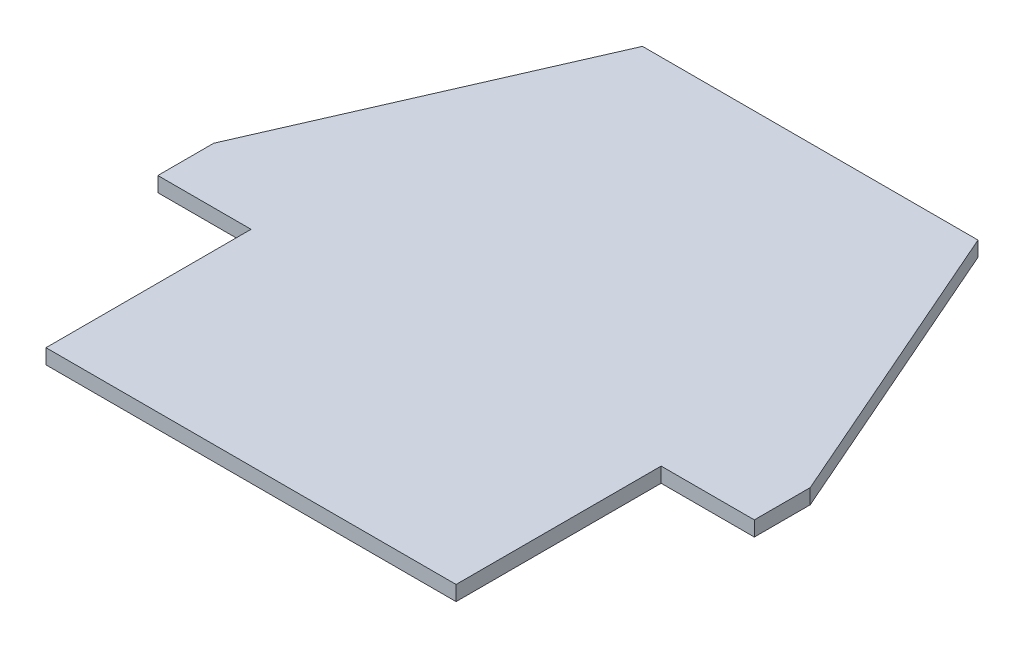
SolidWorks part; units mm, degrees
ref_plane "Alzado" through (0, 0, 0) normal (0, 0, 1) x (1, 0, 0)
ref_plane "Planta" through (0, 0, 0) normal (0, 1, 0) x (1, 0, 0)
ref_plane "Vista lateral" through (0, 0, 0) normal (1, 0, 0) x (0, 0, -1)
sketch "Croquis1" plane through (0, 0, 0) normal (0, 1, 0) x (1, 0, 0)
  line L0 (0, -196.1598) -> (0, 9611.8324) construction
  line L1 (80, 0) -> (-80, 0)
  line L2 (80, 0) -> (80, 70)
  line L3 (80, 70) -> (45, 150)
  line L4 (45, 150) -> (-45, 150)
  line L5 (-80, 0) -> (-80, 70)
  line L6 (-80, 70) -> (-45, 150)
  line L7 (80, 55) -> (55, 55)
  line L8 (55, 55) -> (55, 0)
  line L9 (-55, 55) -> (-55, 0)
  line L10 (-80, 55) -> (-55, 55)
  dimension "D1" = 160
  dimension "D2" = 90
  dimension "D3" = 150
  dimension "D4" = 80
  dimension "D5" = 55
  dimension "D6" = 25
extrude "Saliente-Extruir1" add sketch "Croquis1" along normal mid plane 4 contours L1 L0 L4 L6 L5 L10 L9 | L0 L1 L8 L7 L2 L3 L4
